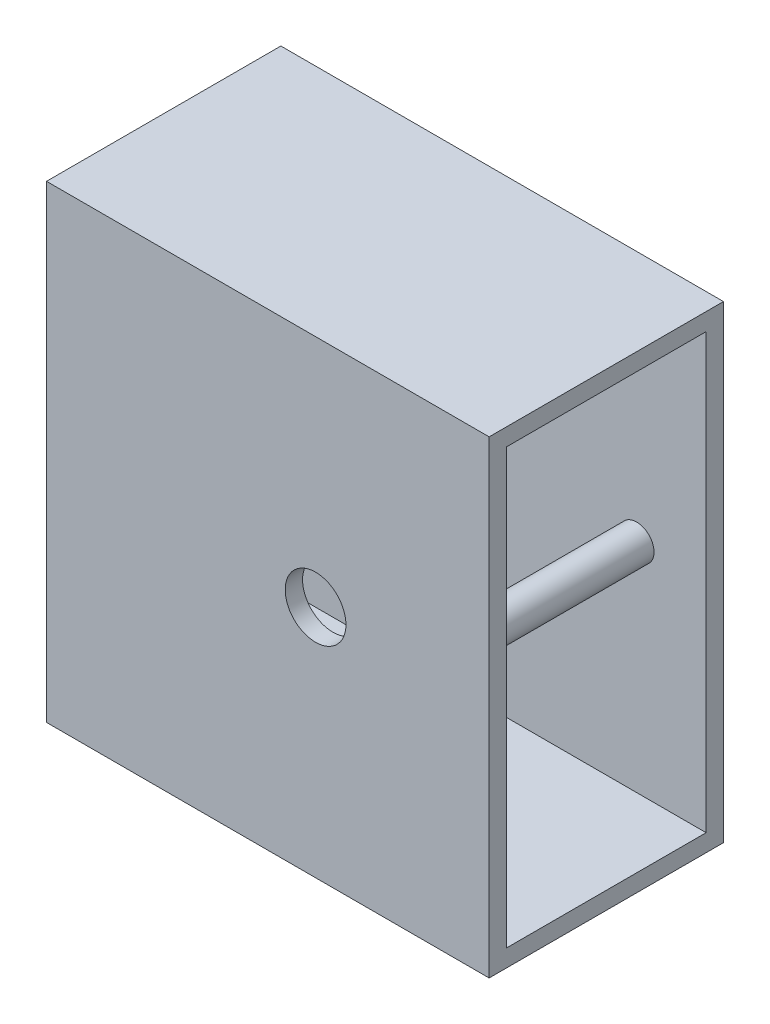
SolidWorks part; units mm, degrees
ref_plane "前视基准面" through (0, 0, 0) normal (0, 0, 1) x (1, 0, 0)
ref_plane "上视基准面" through (0, 0, 0) normal (0, 1, 0) x (1, 0, 0)
ref_plane "右视基准面" through (0, 0, 0) normal (1, 0, 0) x (0, 0, -1)
sketch "草图1" plane through (0, 0, 0) normal (1, 0, 0) x (0, 0, -1)
  line L1 (-11.5, -25) -> (11.5, -25)
  line L2 (-11.5, -25) -> (-11.5, 25)
  line L3 (-11.5, 25) -> (11.5, 25)
  line L4 (11.5, -25) -> (11.5, 25)
  line L5 (-11.5, -25) -> (11.5, 25) construction
  line L6 (-11.5, 25) -> (11.5, -25) construction
  line L7 (-13.5, -27) -> (13.5, -27)
  line L8 (-13.5, -27) -> (-13.5, 27)
  line L9 (-13.5, 27) -> (13.5, 27)
  line L10 (13.5, -27) -> (13.5, 27)
  line L11 (-13.5, -27) -> (13.5, 27) construction
  line L12 (-13.5, 27) -> (13.5, -27) construction
  point P0 (0, 0)
  point P6 (0, 0)
  dimension "D1" = 23
  dimension "D2" = 50
  dimension "D3" = 2
  dimension "D4" = 2
extrude "凸台-拉伸1" add sketch "草图1" along normal blind 50
sketch "草图2" plane through (0, 0, 13.5) normal (0, 0, 1) x (1, 0, 0)
  line L0 (30, 0) -> (0, 0) construction
  line L1 (0, 27) -> (0, -27) construction
  circle A0 centre (30, 0) radius 3.5
  dimension "D1" = 7
  dimension "D2" = 30
extrude "切除-拉伸1" cut sketch "草图2" against normal blind 5
sketch "草图3" plane through (0, 0, 13.5) normal (0, 0, 1) x (1, 0, 0)
  circle A0 centre (42, 0) radius 2
  circle A1 centre (30, 0) radius 3.5 construction
  dimension "D1" = 4
  dimension "D2" = 12
extrude "凸台-拉伸2" add sketch "草图3" against normal blind 25
sketch "草图4" plane through (0, 0, 0) normal (-1, 0, 0) x (0, 0, 1)
  line L4 (-13.5, 27) -> (-13.5, -27)
  line L5 (-13.5, -27) -> (13.5, -27)
  line L6 (13.5, -27) -> (13.5, 27)
  line L7 (13.5, 27) -> (-13.5, 27)
  line L8 (-13.5, 27) -> (-13.5, -27)
  line L9 (-13.5, -27) -> (13.5, -27)
  line L10 (13.5, -27) -> (13.5, 27)
  line L11 (13.5, 27) -> (-13.5, 27)
  dimension "D1" = 0
extrude "凸台-拉伸3" add sketch "草图4" along normal blind 1
